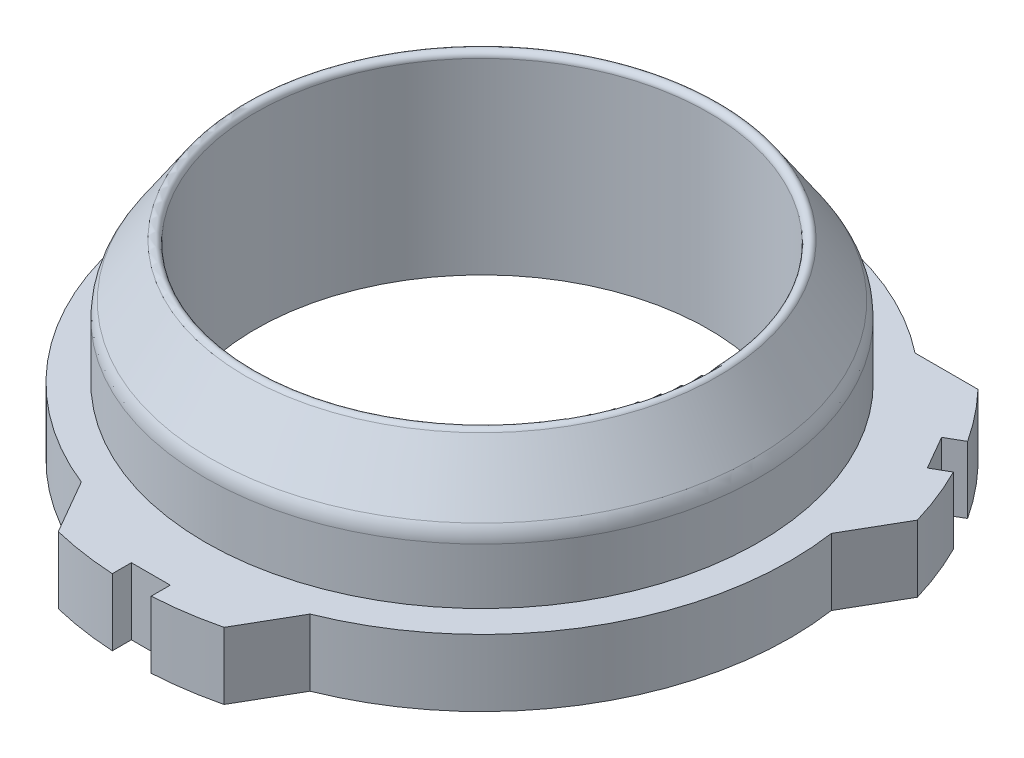
SolidWorks part; units mm, degrees
ref_plane "Front Plane" through (0, 0, 0) normal (0, 0, 1) x (1, 0, 0)
ref_plane "Top Plane" through (0, 0, 0) normal (0, 1, 0) x (1, 0, 0)
ref_plane "Right Plane" through (0, 0, 0) normal (1, 0, 0) x (0, 0, -1)
sketch "Sketch1" plane through (0, 0, 0) normal (0, 1, 0) x (1, 0, 0)
  circle A0 centre (0, 0) radius 33.3375
  circle A1 centre (0, 0) radius 21.5265
extrude "Boss-Extrude1" add sketch "Sketch1" along normal blind 6.35
sketch "Sketch2" plane through (0, 0, 0) normal (0, 0, 1) x (1, 0, 0)
  line L0 (0, 21.2247) -> (0, -9.1987) construction
  line L3 (33.3375, 6.35) -> (-33.3375, 6.35) construction
  line L4 (21.5265, 6.35) -> (21.5265, 17.8236)
  line L5 (22.4557, 18.1076) -> (25.8548, 13.0682)
  line L6 (26.289, 11.6479) -> (26.289, 6.35)
  line L7 (21.5265, 6.35) -> (-21.5265, 6.35) construction
  line L8 (26.289, 6.35) -> (21.5265, 6.35)
  arc A0 (25.8548, 13.0682) -> (26.289, 11.6479) centre (23.749, 11.6479) cw
  arc A1 (21.5265, 17.8236) -> (22.4557, 18.1076) centre (22.0345, 17.8236) cw
  dimension "D2" = 2.54
  dimension "D3" = 0.508
  dimension "D4" = 21.5265
  dimension "D5" = 4.7625
revolve "Revolve1" add sketch "Sketch2" angle 360 about L0
sketch "Sketch3" plane through (0, 0, 0) normal (0, 1, 0) x (1, 0, 0)
  line L0 (0, -33.3375) -> (28.8711, 16.6687)
  line L1 (28.8711, 16.6687) -> (-28.8711, 16.6687)
  line L2 (-28.8711, 16.6687) -> (0, -33.3375)
  line L3 (-24.1149, 23.0187) -> (24.1149, 23.0187)
  line L4 (31.9922, 9.3747) -> (7.8774, -32.3934)
  line L5 (-31.9922, 9.3747) -> (-7.8774, -32.3934)
  circle A0 centre (0, 0) radius 33.3375 construction
  circle A1 centre (0, 0) radius 29.304
  circle A2 centre (0, 0) radius 33.3375
  dimension "D1" = 60
  dimension "D2" = 60
  dimension "D3" = 6.35
  dimension "D4" = 6.35
  dimension "D5" = 6.35
sketch "Sketch5" plane through (0, 0, 0) normal (0, 1, 0) x (1, 0, 0)
  line L0 (-24.1149, 23.0187) -> (24.1149, 23.0187) construction
  line L1 (31.9922, 9.3747) -> (7.8774, -32.3934) construction
  line L2 (-31.9922, 9.3747) -> (-7.8774, -32.3934) construction
  line L3 (-24.1149, 23.0187) -> (-18.1345, 23.0187)
  line L4 (18.1345, 23.0187) -> (24.1149, 23.0187)
  line L5 (31.9922, 9.3747) -> (29.0021, 4.1956)
  line L6 (10.8675, -27.2144) -> (7.8774, -32.3934)
  line L7 (-7.8774, -32.3934) -> (-10.8675, -27.2144)
  line L8 (-29.0021, 4.1956) -> (-31.9922, 9.3747)
  arc A0 (-31.9922, 9.3747) -> (-24.1149, 23.0187) centre (0, 0) cw
  arc A1 (31.9922, 9.3747) -> (24.1149, 23.0187) centre (0, 0) ccw
  arc A2 (-7.8774, -32.3934) -> (7.8774, -32.3934) centre (0, 0) ccw
  arc A3 (-18.1345, 23.0187) -> (18.1345, 23.0187) centre (0, 0) cw
  circle A4 centre (0, 0) radius 29.304 construction
  arc A5 (29.0021, 4.1956) -> (10.8675, -27.2144) centre (0, 0) cw
  arc A6 (-10.8675, -27.2144) -> (-29.0021, 4.1956) centre (0, 0) cw
  circle A7 centre (0, 0) radius 39.889
extrude "Cut-Extrude2" cut sketch "Sketch5" along normal blind 6.35
sketch "Sketch6" plane through (0, 0, 0) normal (0, 1, 0) x (1, 0, 0)
  line L0 (-28.1835, 14.1367) -> (-31.4078, 15.9983)
  line L1 (-1.849, -31.476) -> (1.849, -31.476)
  line L2 (-1.849, -31.476) -> (-1.849, -35.199)
  line L3 (-1.849, -35.199) -> (1.849, -35.199)
  line L4 (1.849, -31.476) -> (1.849, -35.199)
  line L5 (-1.849, -31.476) -> (1.849, -35.199) construction
  line L6 (-1.849, -35.199) -> (1.849, -31.476) construction
  line L7 (-26.3345, 17.3392) -> (-28.1835, 14.1367)
  line L8 (-26.3345, 17.3392) -> (-29.5588, 19.2008)
  line L9 (-29.5588, 19.2008) -> (-31.4078, 15.9983)
  line L10 (26.3345, 17.3392) -> (29.5588, 19.2008)
  line L11 (28.1835, 14.1367) -> (26.3345, 17.3392)
  line L12 (28.1835, 14.1367) -> (31.4078, 15.9983)
  line L13 (31.4078, 15.9983) -> (29.5588, 19.2008)
  point P0 (0, -33.3375)
  dimension "D1" = 3
extrude "Cut-Extrude3" cut sketch "Sketch6" along normal blind 6.35
sketch "Sketch7" plane through (0, 0, 0) normal (0, 0, 1) x (1, 0, 0)
  line L0 (0, 32.3698) -> (0, -14.474) construction
  line L1 (-40.3801, 0) -> (39.7265, 0) construction
